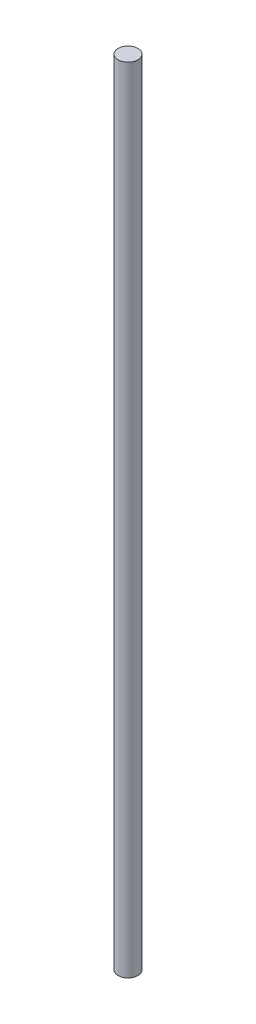
SolidWorks part; units mm, degrees
ref_plane "Front Plane" through (0, 0, 0) normal (0, 0, 1) x (1, 0, 0)
ref_plane "Top Plane" through (0, 0, 0) normal (0, 1, 0) x (1, 0, 0)
ref_plane "Right Plane" through (0, 0, 0) normal (1, 0, 0) x (0, 0, -1)
sketch "Sketch1" plane through (0, 0, 0) normal (0, 0, 1) x (1, 0, 0)
  line L0 (5, 400) -> (0, 400)
  line L1 (0, 400) -> (0, 0)
  line L2 (0, 0) -> (5, 0)
  line L3 (5, 0) -> (5, 400)
  line L4 (0, 400) -> (0, 0) construction
  dimension "D1" = 400
  dimension "D2" = 5
revolve "Revolve1" add sketch "Sketch1" angle 360 about L4
